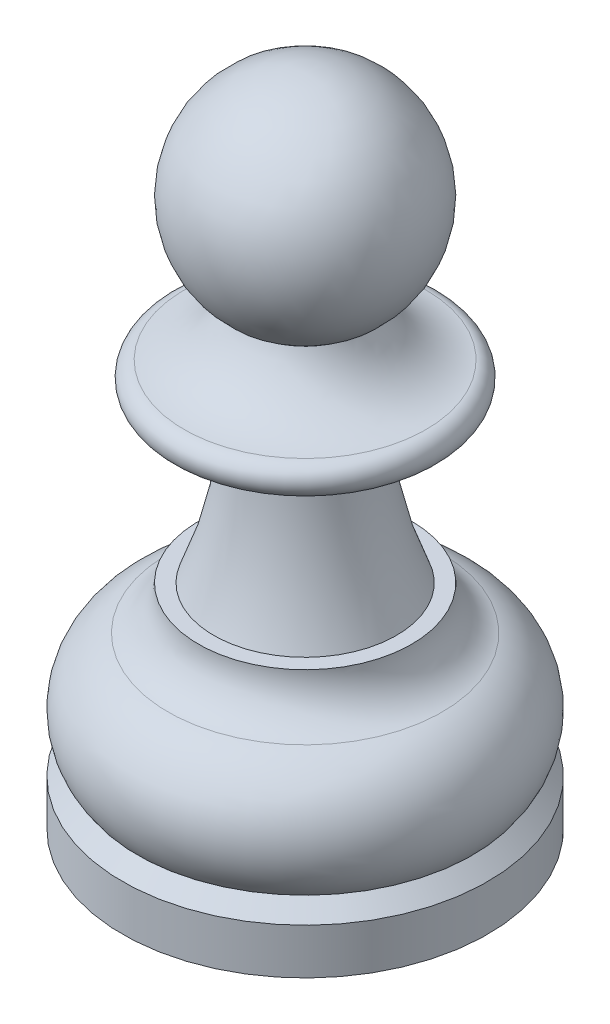
SolidWorks part; units mm, degrees
ref_plane "Front Plane" through (0, 0, 0) normal (0, 0, 1) x (1, 0, 0)
ref_plane "Top Plane" through (0, 0, 0) normal (0, 1, 0) x (1, 0, 0)
ref_plane "Right Plane" through (0, 0, 0) normal (1, 0, 0) x (0, 0, -1)
sketch "Sketch1" plane through (0, 0, 0) normal (1, 0, 0) x (0, 0, -1)
  line L0 (0, 0) -> (0, 43)
  line L1 (0, 0) -> (12, 0)
  line L2 (12, 0) -> (12, 3)
  line L3 (12, 3) -> (11, 4)
  line L4 (4, 24) -> (8, 24.7053)
  line L5 (4, 24) -> (-1000, 24) construction
  line L6 (6, 14) -> (7, 14)
  arc A0 (11, 4) -> (9, 11.1407) centre (7.4341, 6.8516) ccw
  arc A1 (3.6056, 30) -> (0, 43) centre (0, 36) ccw
  arc A2 (8, 24.7053) -> (7.9437, 26.6832) centre (7.8264, 25.6901) ccw
  arc A3 (3.6056, 30) -> (7.9437, 26.6832) centre (8.5722, 32.0007) ccw
  arc A4 (7, 14) -> (9, 11.1407) centre (10.044, 14) ccw
  arc A6 (4, 24) -> (6, 14) centre (30, 24) ccw
  point P9 (3.6056, 30)
  point P11 (4, 24)
  point P12 (8, 24.7053)
  point P25 (8.6529, 9.1575)
  dimension "D6" = 1
  dimension "D7" = 7
  dimension "D13" = 2
  dimension "D14" = 14
  dimension "D15" = 6
  dimension "D16" = 5.3545
  dimension "D1" = 43
  dimension "D2" = 12
  dimension "D3" = 3
  dimension "D4" = 1
  dimension "D5" = 45
  dimension "D8" = 30
  dimension "D9" = 4
  dimension "D10" = 24
  dimension "D11" = 8
  dimension "D12" = 10
  dimension "D17" = 9
revolve "Revolve1" add sketch "Sketch1" angle 360 about L0
